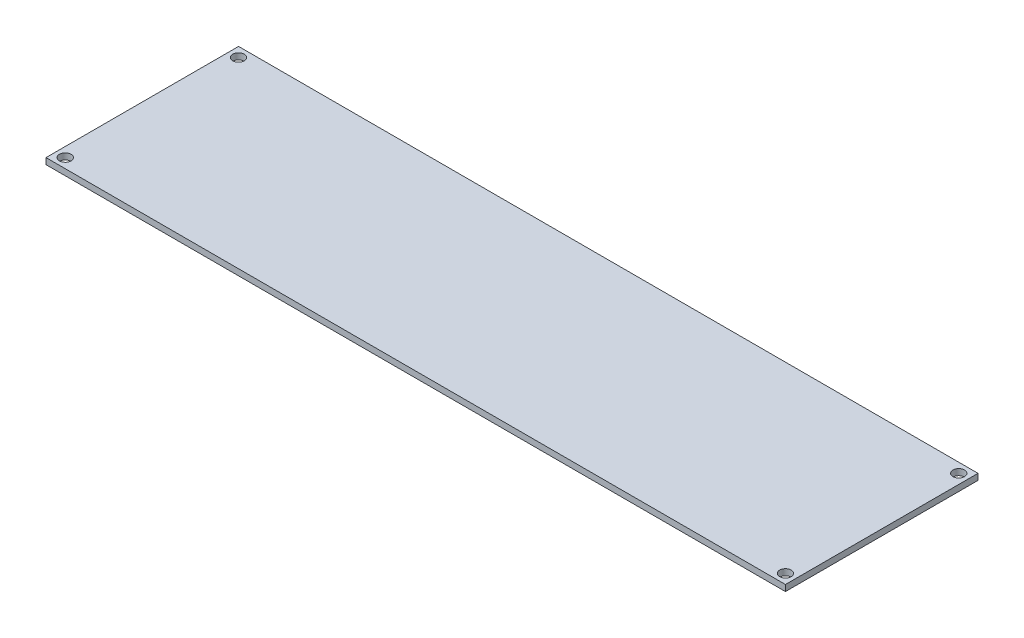
SolidWorks part; units mm, degrees
ref_plane "Front Plane" through (0, 0, 0) normal (0, 0, 1) x (1, 0, 0)
ref_plane "Top Plane" through (0, 0, 0) normal (0, 1, 0) x (1, 0, 0)
ref_plane "Right Plane" through (0, 0, 0) normal (1, 0, 0) x (0, 0, -1)
sketch "Sketch1" plane through (0, 0, 0) normal (0, 1, 0) x (1, 0, 0)
  line L1 (0, 0) -> (192, 0)
  line L2 (0, 0) -> (0, 50)
  line L3 (0, 50) -> (192, 50)
  line L4 (192, 0) -> (192, 50)
  dimension "D1" = 192
  dimension "D2" = 50
extrude "Boss-Extrude1" add sketch "Sketch1" along normal blind 1.6
sketch "Sketch2" plane through (0, 0, 0) normal (0, -1, 0) x (1, 0, 0)
  line L0 (0, 0) -> (192, 0) construction
  line L1 (0, -50) -> (0, 0) construction
  line L2 (192, 0) -> (192, -50) construction
  line L3 (192, -50) -> (0, -50) construction
  circle A0 centre (2.5, -2.5) radius 1.5
  circle A1 centre (189.5, -2.5) radius 1.5
  circle A2 centre (189.5, -47.5) radius 1.5
  circle A3 centre (2.5, -47.5) radius 1.5
  dimension "D1" = 3
  dimension "D2" = 3
  dimension "D3" = 3
  dimension "D4" = 3
  dimension "D5" = 2.5
  dimension "D6" = 2.5
  dimension "D7" = 2.5
  dimension "D8" = 2.5
  dimension "D9" = 2.5
  dimension "D10" = 2.5
  dimension "D11" = 2.5
  dimension "D12" = 2.5
extrude "Cut-Extrude1" cut sketch "Sketch2" against normal blind 1.6
